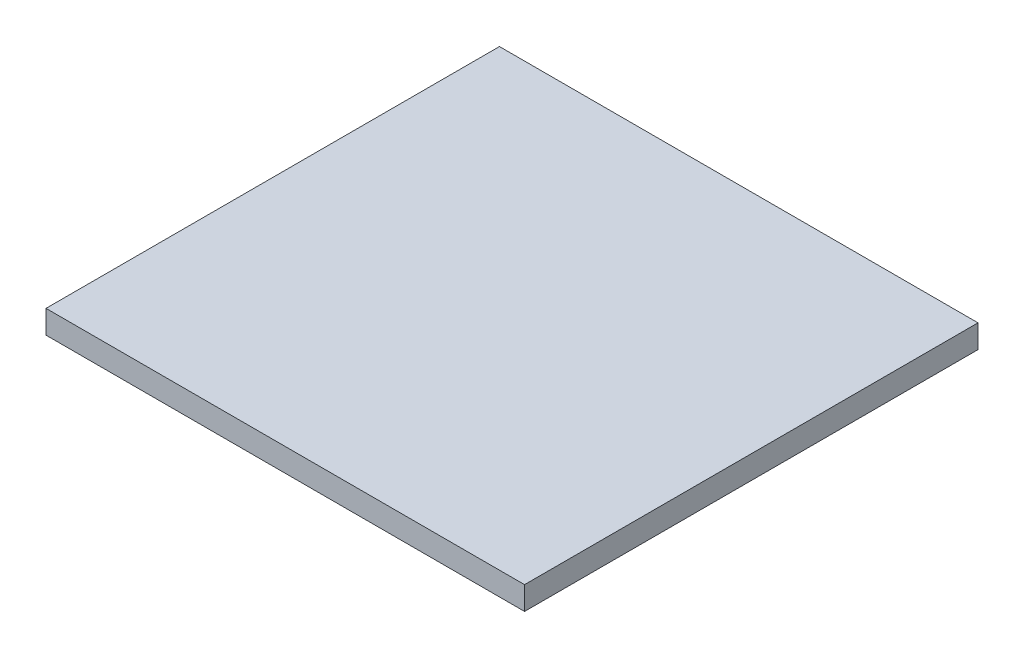
SolidWorks part; units mm, degrees
material "Pine"
ref_plane "Front Plane" through (0, 0, 0) normal (0, 0, 1) x (1, 0, 0)
ref_plane "Top Plane" through (0, 0, 0) normal (0, 1, 0) x (1, 0, 0)
ref_plane "Right Plane" through (0, 0, 0) normal (1, 0, 0) x (0, 0, -1)
sketch "Sketch1" plane through (0, 0, 0) normal (0, 1, 0) x (1, 0, 0)
  line L1 (-65.9453, 79.2259) -> (64.8647, 79.2259)
  line L2 (-65.9453, 79.2259) -> (-65.9453, -44.7261)
  line L3 (-65.9453, -44.7261) -> (64.8647, -44.7261)
  line L4 (64.8647, 79.2259) -> (64.8647, -44.7261)
  dimension "D1" = 130.81
  dimension "D2" = 123.952
extrude "Boss-Extrude1" add sketch "Sketch1" along normal blind 6.35
ref_plane "Plane1" through (-65.9453, 6.35, -79.2259) normal (-1, 0, 0) x (0, 0, 1)
sketch "Sketch3" plane through (0, 6.35, 0) normal (0, 1, 0) x (1, 0, 0)
  line L0 (64.8647, -44.7261) -> (64.8647, 79.2259) construction
  line L1 (-65.9453, 79.2259) -> (64.8647, 79.2259)
  line L2 (-65.9453, 79.2259) -> (-65.9453, 63.3509)
  line L3 (-65.9453, 63.3509) -> (64.8647, 63.3509)
  line L4 (64.8647, 79.2259) -> (64.8647, 63.3509)
  line L6 (-65.9453, -44.7261) -> (64.8647, -44.7261)
  line L7 (-65.9453, -44.7261) -> (-65.9453, -28.8511)
  line L8 (-65.9453, -28.8511) -> (64.8647, -28.8511)
  line L9 (64.8647, -44.7261) -> (64.8647, -28.8511)
  dimension "D1" = 15.875
  dimension "D2" = 15.875
extrude "Boss-Extrude2" [suppressed] add sketch "Sketch3" along normal blind 25.4 contours L2 L1 L4 L3 | L7 L6 L9 L8
